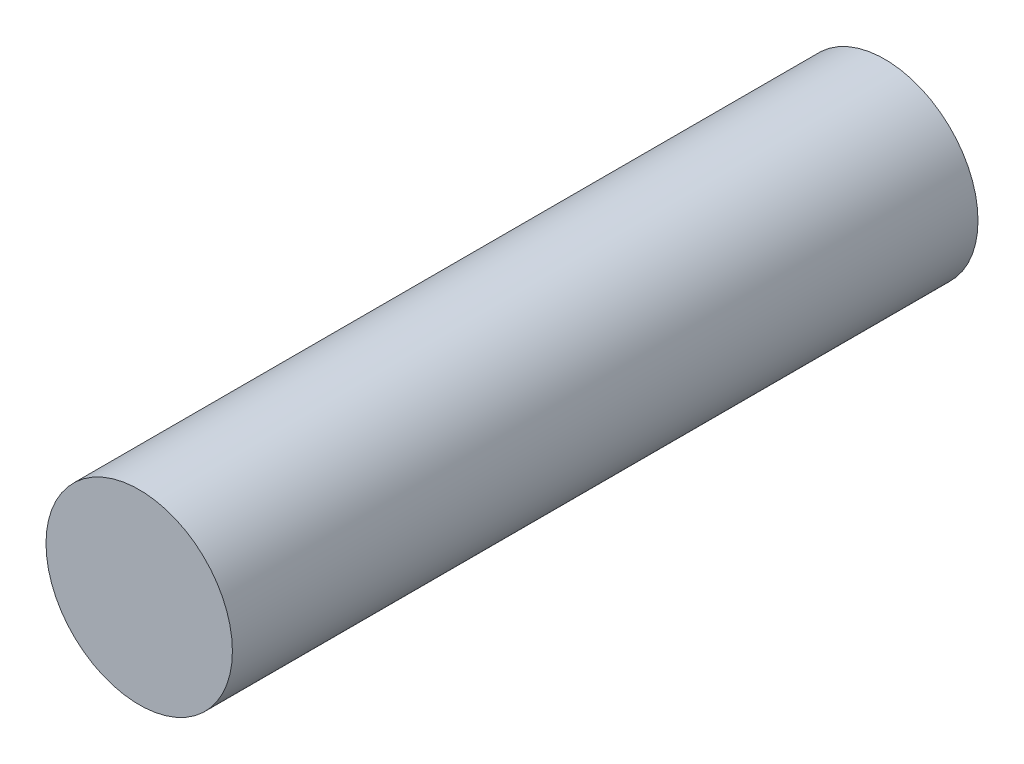
SolidWorks part; units mm, degrees
ref_plane "Plan de face" through (0, 0, 0) normal (0, 0, 1) x (1, 0, 0)
ref_plane "Plan de dessus" through (0, 0, 0) normal (0, 1, 0) x (1, 0, 0)
ref_plane "Plan de droite" through (0, 0, 0) normal (1, 0, 0) x (0, 0, -1)
sketch "Esquisse1" plane through (0, 0, 0) normal (0, 0, 1) x (1, 0, 0)
  circle A0 centre (0, 0) radius 1.5
  dimension "D1" = 3
extrude "Boss.-Extru.1" add sketch "Esquisse1" along normal blind 12
